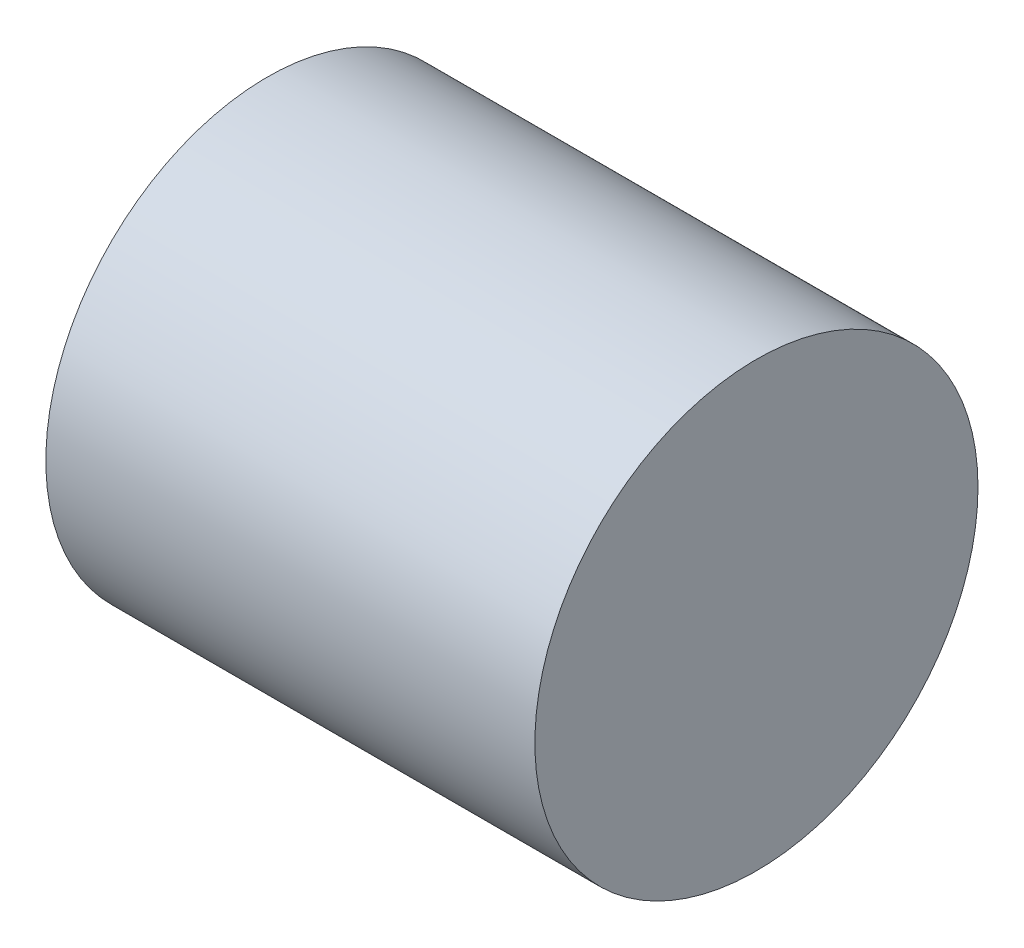
SolidWorks part; units mm, degrees
ref_plane "Front Plane" through (0, 0, 0) normal (0, 0, 1) x (1, 0, 0)
ref_plane "Top Plane" through (0, 0, 0) normal (0, 1, 0) x (1, 0, 0)
ref_plane "Right Plane" through (0, 0, 0) normal (1, 0, 0) x (0, 0, -1)
sketch "CurveSketch" plane through (0, 0, 0) normal (1, 0, 0) x (0, 0, -1)
  circle A0 centre (9.173, -2.419) radius 9.3293
  dimension "D1" = 9.3293
extrude "CurveBoss" add sketch "CurveSketch" against normal blind 20.5919
